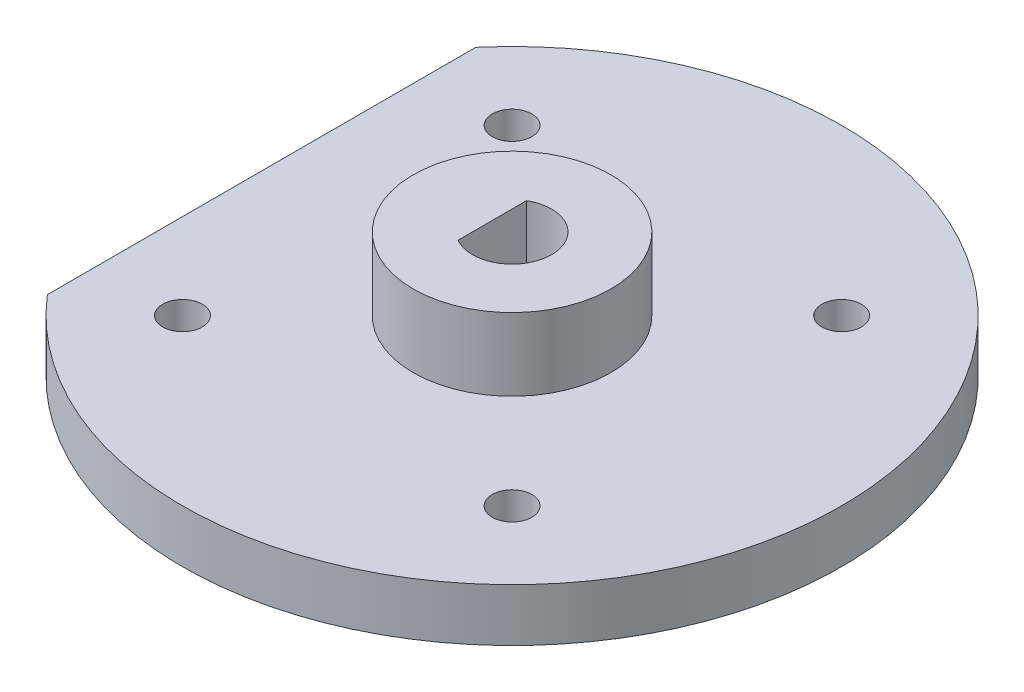
SolidWorks part; units mm, degrees
ref_plane "Front Plane" through (0, 0, 0) normal (0, 0, 1) x (1, 0, 0)
ref_plane "Top Plane" through (0, 0, 0) normal (0, 1, 0) x (1, 0, 0)
ref_plane "Right Plane" through (0, 0, 0) normal (1, 0, 0) x (0, 0, -1)
sketch "Sketch1" plane through (0, 0, 0) normal (0, 1, 0) x (1, 0, 0)
  line L0 (-3, 3) -> (-3, -3) construction
  line L1 (-1.5, 2.5981) -> (-1.5, -2.5981)
  line L2 (-1.5, 3) -> (-1.5, -3) construction
  line L3 (-25, 0) -> (-19, 0) construction
  line L4 (-12.5, 12.5) -> (12.5, 12.5) construction
  line L5 (-12.5, 12.5) -> (-12.5, -12.5) construction
  line L6 (-12.5, -12.5) -> (12.5, -12.5) construction
  line L7 (12.5, 12.5) -> (12.5, -12.5) construction
  line L8 (-12.5, 12.5) -> (12.5, -12.5) construction
  line L9 (-12.5, -12.5) -> (12.5, 12.5) construction
  line L10 (-19, 16.2481) -> (-19, -16.2481)
  line L11 (-25, 11.5492) -> (-25, -11.5492) construction
  arc A0 (-19, -16.2481) -> (-19, 16.2481) centre (0, 0) ccw
  arc A1 (-1.5, -2.5981) -> (-1.5, 2.5981) centre (0, 0) ccw
  circle A2 centre (12.5, 12.5) radius 1.5
  circle A3 centre (12.5, -12.5) radius 1.5
  circle A4 centre (-12.5, -12.5) radius 1.5
  circle A5 centre (-12.5, 12.5) radius 1.5
  point P7 (-3, 0)
  point P23 (-19, 0)
  point P26 (-25, 0)
  dimension "D1" = 50
  dimension "D2" = 6
  dimension "D7" = 3
  dimension "D8" = 3
  dimension "D9" = 3
  dimension "D10" = 3
  dimension "D3" = 6
  dimension "D5" = 25
  dimension "D6" = 25
  dimension "D11" = 6
  dimension "D12" = 32.4962
  dimension "D4" = 1.5
extrude "Boss-Extrude1" add sketch "Sketch1" along normal blind 4
sketch "Sketch2" plane through (0, 4, 0) normal (0, 1, 0) x (1, 0, 0)
  line L0 (-1.5, 2.5981) -> (-1.5, -2.5981)
  circle A0 centre (0, 0) radius 7.5
  arc A1 (-1.5, -2.5981) -> (-1.5, 2.5981) centre (0, 0) ccw
  dimension "D1" = 15
  dimension "D2" = 3
extrude "Boss-Extrude2" add sketch "Sketch2" along normal blind 5.5
